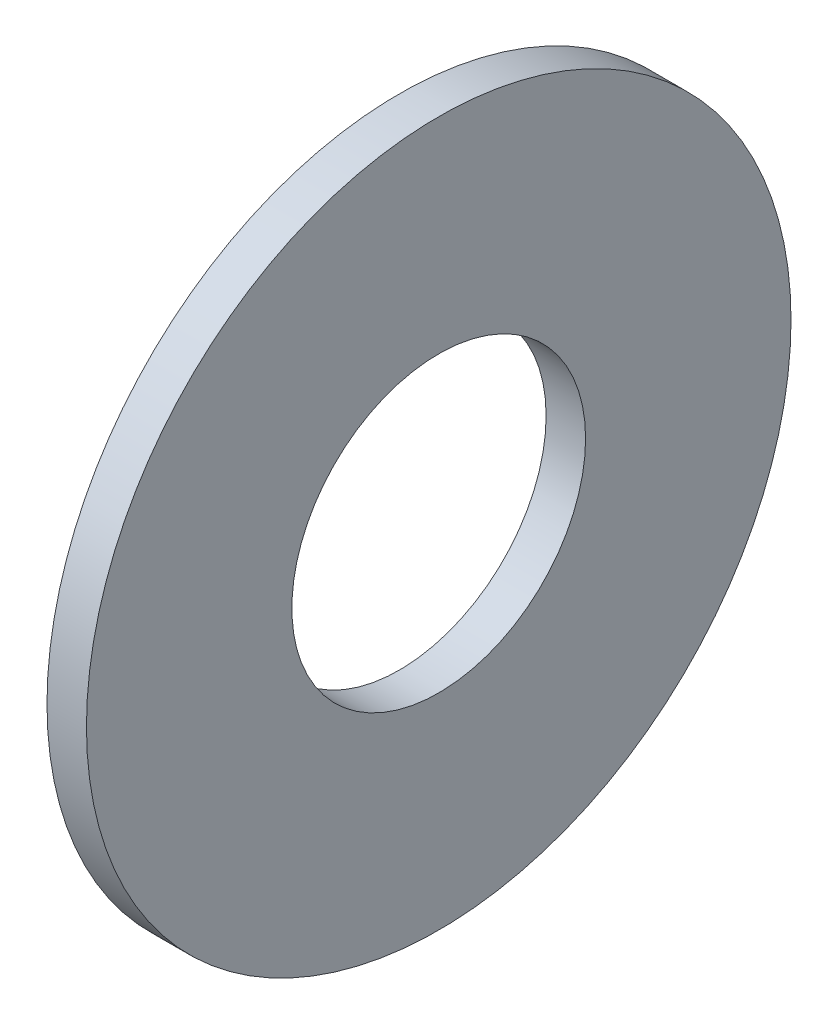
SolidWorks part; units mm, degrees
ref_plane "Front Plane" through (0, 0, 0) normal (0, 0, 1) x (1, 0, 0)
ref_plane "Top Plane" through (0, 0, 0) normal (0, 1, 0) x (1, 0, 0)
ref_plane "Right Plane" through (0, 0, 0) normal (1, 0, 0) x (0, 0, -1)
sketch "Sketch1" plane through (0, 0, 0) normal (1, 0, 0) x (0, 0, -1)
  circle A0 centre (0, 0) radius 5.9563
  circle A1 centre (0, 0) radius 14.2875
  dimension "OD" = 11.9126
  dimension "ID" = 28.575
extrude "Boss-Extrude1" add sketch "Sketch1" along normal blind 1.6002
